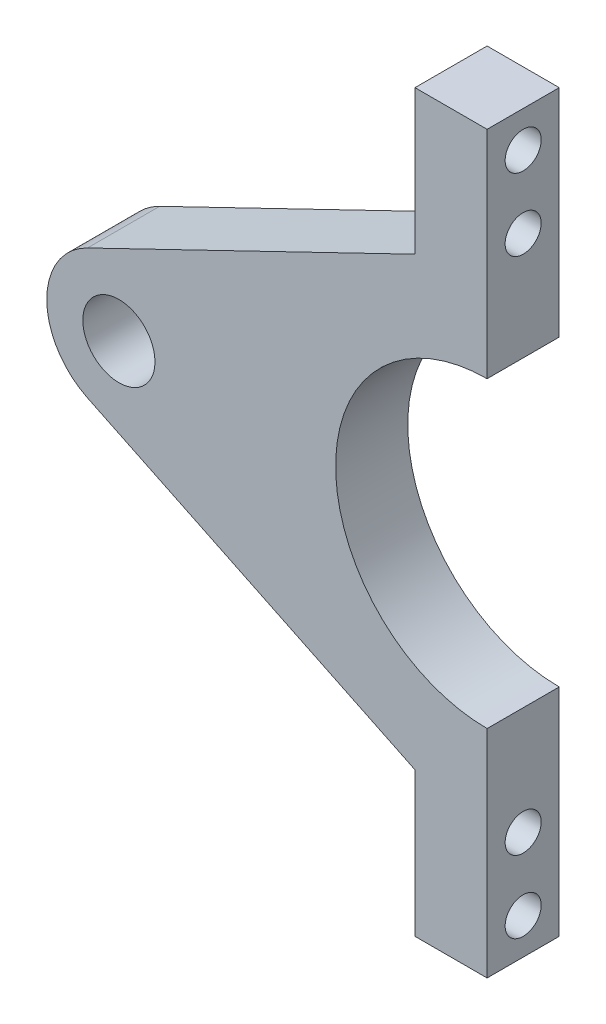
SolidWorks part; units mm, degrees
ref_plane "Front Plane" through (0, 0, 0) normal (0, 0, 1) x (1, 0, 0)
ref_plane "Top Plane" through (0, 0, 0) normal (0, 1, 0) x (1, 0, 0)
ref_plane "Right Plane" through (0, 0, 0) normal (1, 0, 0) x (0, 0, -1)
sketch "Sketch1" plane through (0, 0, 0) normal (0, 0, 1) x (1, 0, 0)
  line L0 (0, 24.2997) -> (0, 54.25)
  line L1 (0, 54.25) -> (-10, 54.25)
  line L2 (-10, 54.25) -> (-10, 34.25)
  line L3 (-10, 34.25) -> (-55.4002, 12.3029)
  line L4 (-24.0245, 3.2997) -> (-74.0245, 3.2997) construction
  line L5 (0, -17.7003) -> (0, -47.6506)
  line L6 (0, -47.6506) -> (-10, -47.6506)
  line L7 (-10, -47.6506) -> (-10, -27.6506)
  line L8 (-10, -27.6506) -> (-55.4002, -5.7035)
  arc A2 (-55.4002, 12.3029) -> (-55.4002, -5.7035) centre (-51.048, 3.2997) ccw
  arc A3 (0, 24.2997) -> (0, -17.7003) centre (0, 3.2997) ccw
  point P16 (-61.048, 3.2997)
  dimension "D6" = 10
  dimension "D1" = 42
  dimension "D3" = 10
  dimension "D4" = 20
  dimension "D5" = 50
  dimension "D7" = 37.0235
extrude "Boss-Extrude1" add sketch "Sketch1" against normal blind 10
sketch "Sketch2" plane through (0, 0, 0) normal (0, 0, 1) x (1, 0, 0)
  circle A0 centre (-51.048, 3.2997) radius 5
  dimension "D1" = 10
extrude "Cut-Extrude1" cut sketch "Sketch2" against normal through all
sketch "Sketch3" plane through (-10, 0, 0) normal (-1, 0, 0) x (0, 0, 1)
  line L1 (-10, 54.25) -> (0, 54.25) construction
  circle A0 centre (-5, 49.25) radius 2.5
  circle A1 centre (-5, 39.25) radius 2.5
  circle A2 centre (-5, -32.6506) radius 2.5
  circle A3 centre (-5, -42.6506) radius 2.5
  dimension "D1" = 5
  dimension "D2" = 5
  dimension "D3" = 10
extrude "Cut-Extrude2" cut sketch "Sketch3" against normal through all
